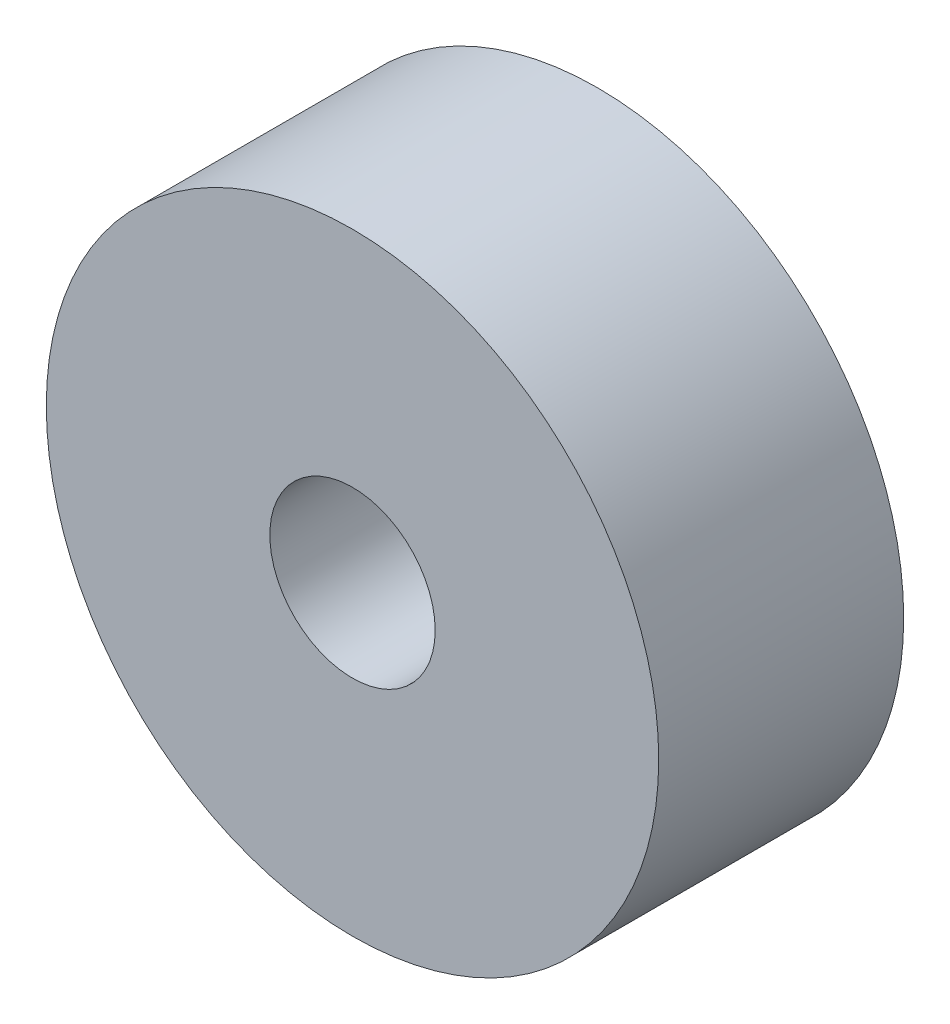
SolidWorks part; units mm, degrees
ref_plane "Front Plane" through (0, 0, 0) normal (0, 0, 1) x (1, 0, 0)
ref_plane "Top Plane" through (0, 0, 0) normal (0, 1, 0) x (1, 0, 0)
ref_plane "Right Plane" through (0, 0, 0) normal (1, 0, 0) x (0, 0, -1)
sketch "Sketch1" plane through (0, 0, 0) normal (0, 0, 1) x (1, 0, 0)
  circle A0 centre (0, 0) radius 25
  circle A1 centre (0, 0) radius 6.75
  dimension "D1" = 50
  dimension "D2" = 13.5
extrude "Boss-Extrude1" add sketch "Sketch1" along normal blind 20
